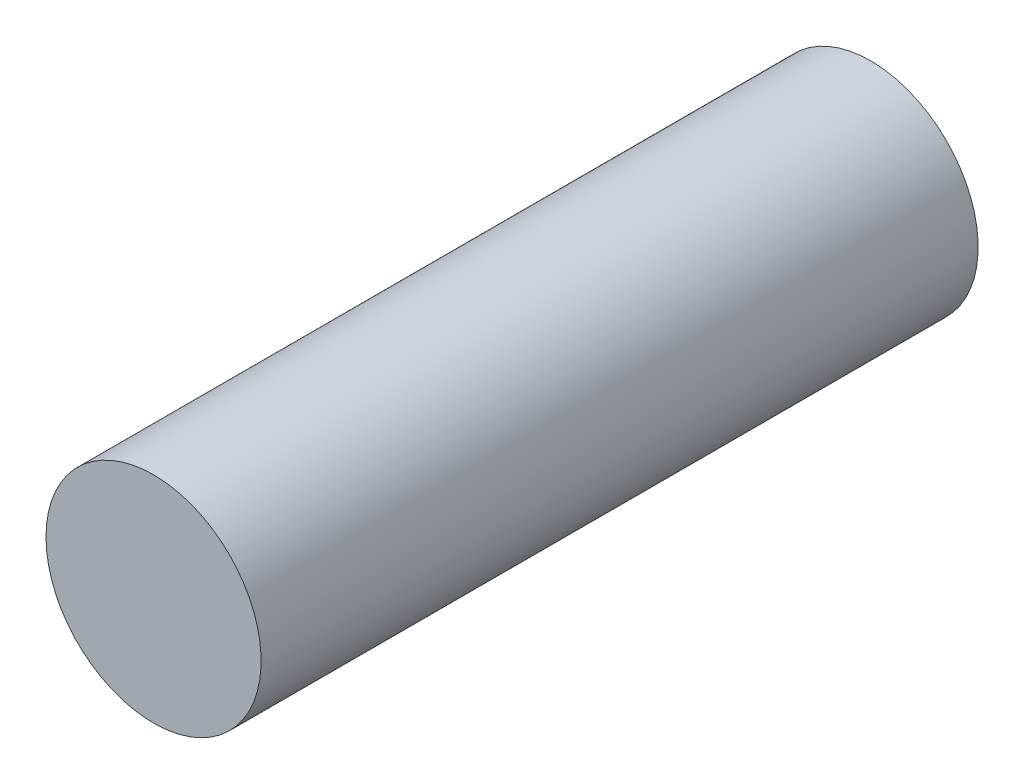
SolidWorks part; units mm, degrees
ref_plane "Front Plane" through (0, 0, 0) normal (0, 0, 1) x (1, 0, 0)
ref_plane "Top Plane" through (0, 0, 0) normal (0, 1, 0) x (1, 0, 0)
ref_plane "Right Plane" through (0, 0, 0) normal (1, 0, 0) x (0, 0, -1)
sketch "Sketch1" plane through (0, 0, 0) normal (0, 0, 1) x (1, 0, 0)
  circle A0 centre (0, 0) radius 2.286
  dimension "D1" = 4.572
extrude "Boss-Extrude1" add sketch "Sketch1" along normal blind 15.24
